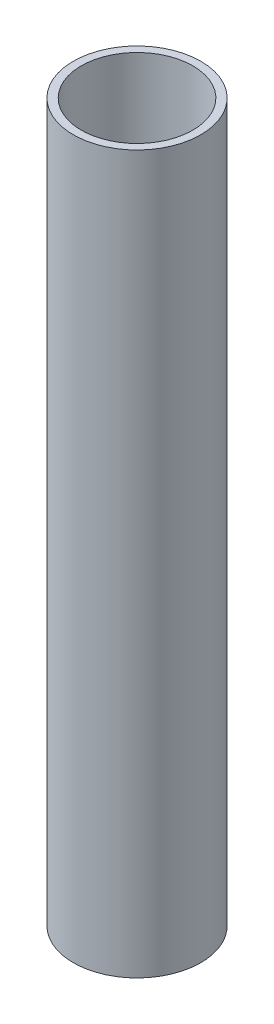
SolidWorks part; units mm, degrees
ref_plane "Front Plane" through (0, 0, 0) normal (0, 0, 1) x (1, 0, 0)
ref_plane "Top Plane" through (0, 0, 0) normal (0, 1, 0) x (1, 0, 0)
ref_plane "Right Plane" through (0, 0, 0) normal (1, 0, 0) x (0, 0, -1)
sketch "Sketch1" plane through (0, 0, 0) normal (0, 1, 0) x (1, 0, 0)
  circle A0 centre (0, 0) radius 8
  circle A1 centre (0, 0) radius 7
extrude "Boss-Extrude1" add sketch "Sketch1" along normal blind 90
